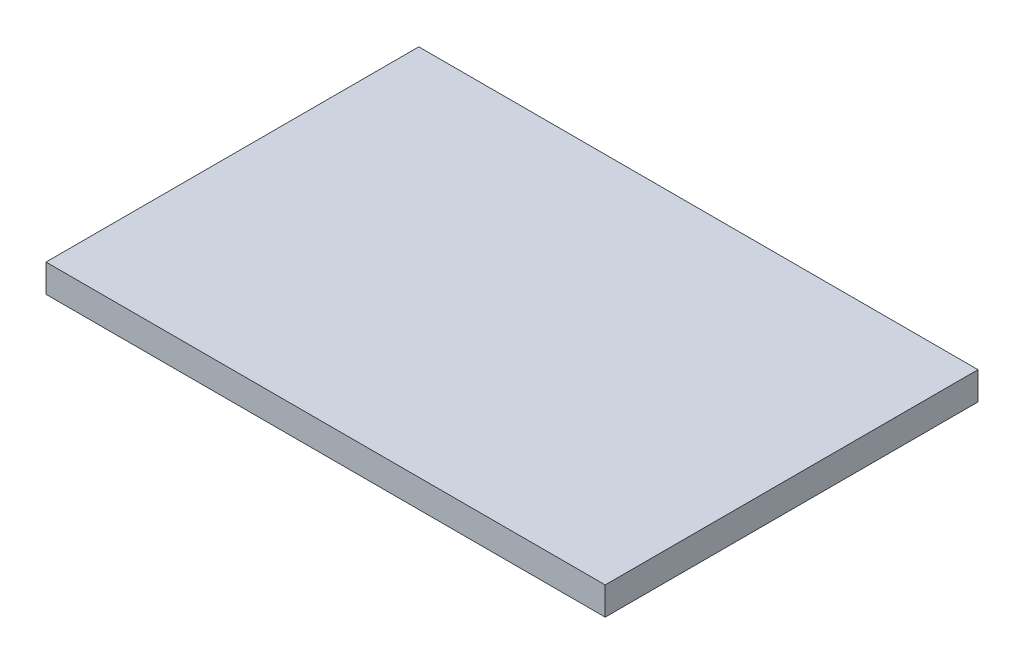
SolidWorks part; units mm, degrees
ref_plane "Plan de face" through (0, 0, 0) normal (0, 0, 1) x (1, 0, 0)
ref_plane "Plan de dessus" through (0, 0, 0) normal (0, 1, 0) x (1, 0, 0)
ref_plane "Plan de droite" through (0, 0, 0) normal (1, 0, 0) x (0, 0, -1)
sketch "Esquisse1" plane through (0, 0, 0) normal (0, 1, 0) x (1, 0, 0)
  line L1 (-30, -20) -> (30, -20)
  line L2 (-30, -20) -> (-30, 20)
  line L3 (-30, 20) -> (30, 20)
  line L4 (30, -20) -> (30, 20)
  line L5 (-30, -20) -> (30, 20) construction
  line L6 (-30, 20) -> (30, -20) construction
  point P0 (0, 0)
  dimension "D1" = 60
  dimension "D2" = 40
extrude "Boss.-Extru.1" add sketch "Esquisse1" along normal blind 3
